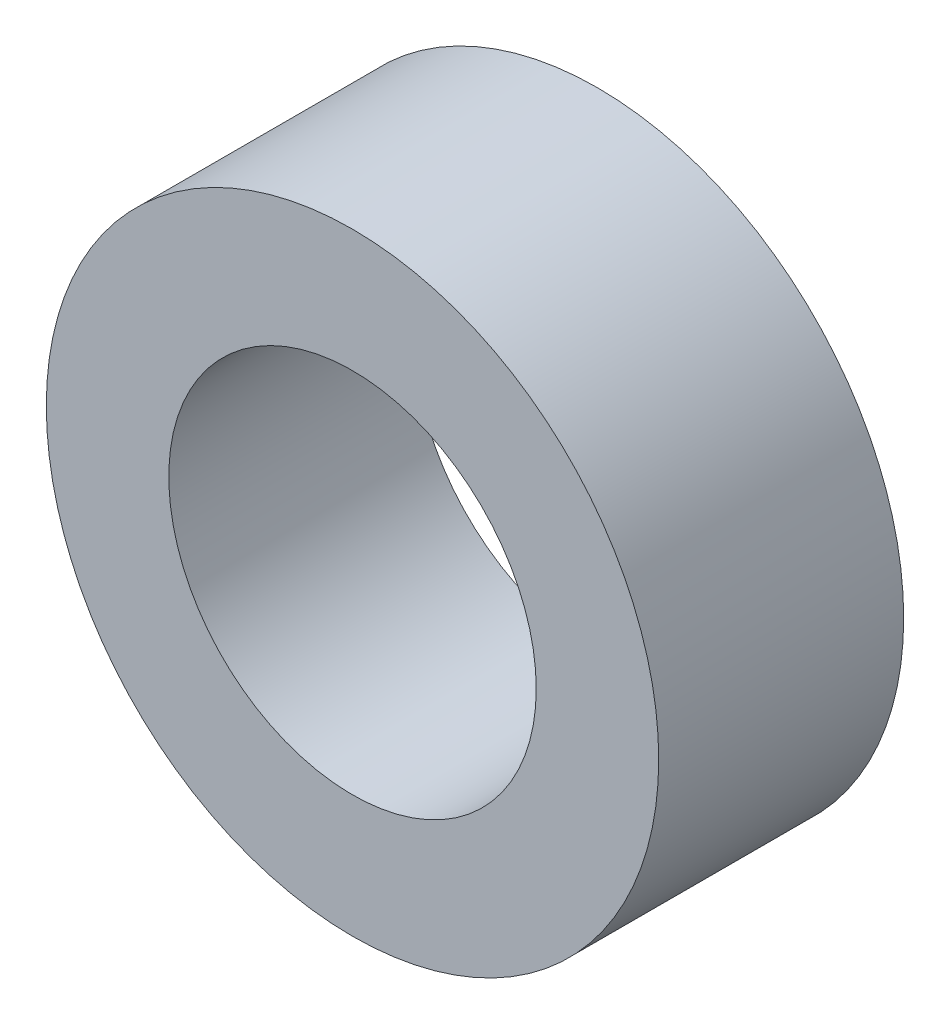
SolidWorks part; units mm, degrees
material "AISI 1045 Steel, cold drawn"
ref_plane "Front" through (0, 0, 0) normal (0, 0, 1) x (1, 0, 0)
ref_plane "Top" through (0, 0, 0) normal (0, 1, 0) x (1, 0, 0)
ref_plane "Right" through (0, 0, 0) normal (1, 0, 0) x (0, 0, -1)
sketch "Sketch1" plane through (0, 0, 0) normal (0, 0, 1) x (1, 0, 0)
  circle A0 centre (0, 0) radius 7.9375
  circle A1 centre (0, 0) radius 4.7625
  dimension "D1" = 15.875
  dimension "D2" = 9.525
extrude "Boss-Extrude1" add sketch "Sketch1" along normal blind 6.35
